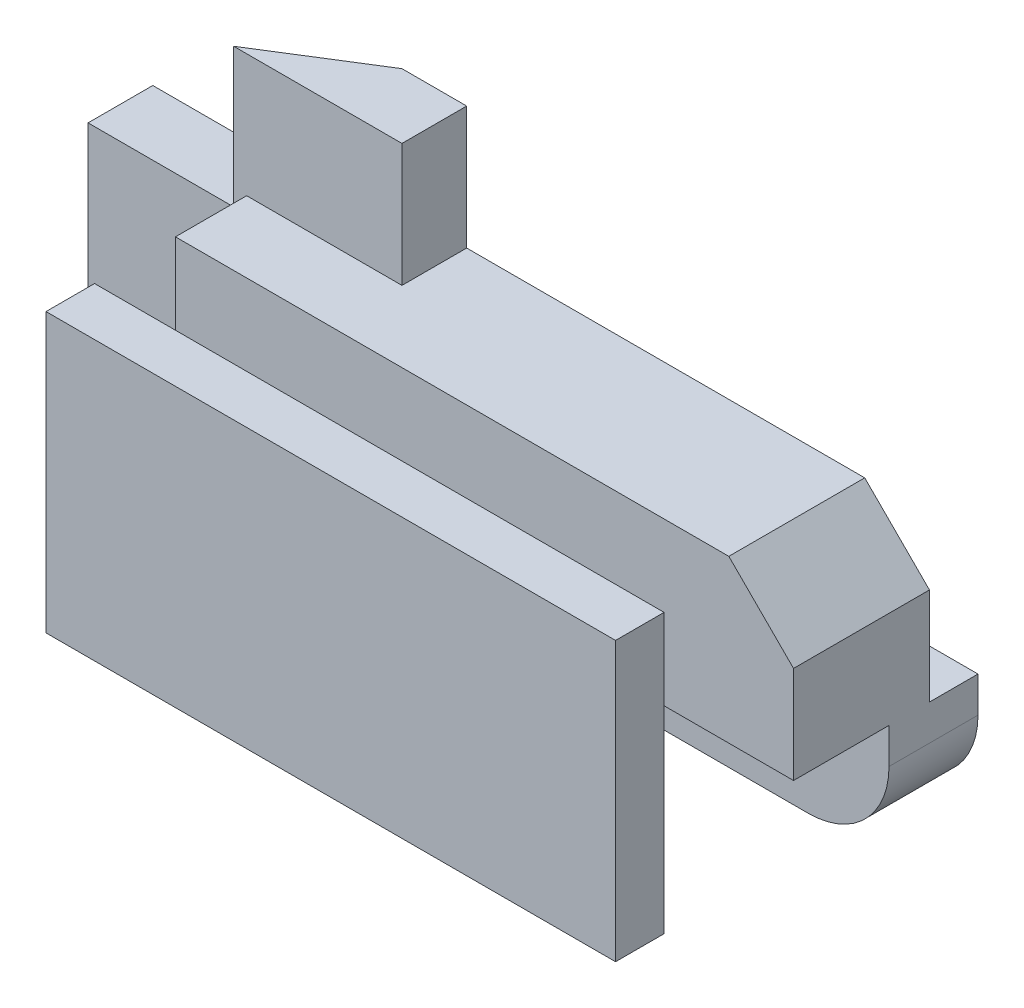
SolidWorks part; units mm, degrees
ref_plane "前视基准面" through (0, 0, 0) normal (0, 0, 1) x (1, 0, 0)
ref_plane "上视基准面" through (0, 0, 0) normal (0, 1, 0) x (1, 0, 0)
ref_plane "右视基准面" through (0, 0, 0) normal (1, 0, 0) x (0, 0, -1)
sketch "草图1" plane through (0, 0, 0) normal (0, 0, 1) x (1, 0, 0)
  line L1 (0, 0) -> (4.5, 0)
  line L2 (0, 0) -> (0, 6)
  line L3 (0, 6) -> (4.5, 6)
  line L4 (4.5, 0) -> (4.5, 6)
  line L5 (0, 0) -> (4.5, 6) construction
  line L6 (0, 6) -> (4.5, 0) construction
  point P4 (2.25, 3)
  dimension "D1" = 6
  dimension "D2" = 4.5
extrude "凸台-拉伸1" add sketch "草图1" along normal blind 2
sketch "草图2" plane through (0, 0, 0) normal (0, 0, -1) x (-1, 0, 0)
  line L0 (0, 6) -> (0, 0) construction
  line L1 (-4.5, 0) -> (-24, 0)
  line L2 (-4.5, 0) -> (-4.5, 6.5)
  line L3 (-4.5, 6.5) -> (-24, 6.5)
  line L4 (-24, 0) -> (-24, 6.5)
  line L5 (-4.5, 0) -> (-24, 6.5) construction
  line L6 (-4.5, 6.5) -> (-24, 0) construction
  point P4 (-14.25, 3.25)
  dimension "D1" = 6.5
  dimension "D2" = 24
extrude "凸台-拉伸2" add sketch "草图2" against normal blind 4.2
sketch "草图4" plane through (0, 0, 0) normal (0, 0, -1) x (-1, 0, 0)
  line L0 (0, 6) -> (0, 0) construction
  line L1 (-24, 0) -> (-14, 0)
  line L2 (-24, 0) -> (-24, -2.1)
  line L3 (-24, -2.1) -> (-14, -2.1)
  line L4 (-14, 0) -> (-14, -2.1)
  line L5 (-24, 0) -> (-14, -2.1) construction
  line L6 (-24, -2.1) -> (-14, 0) construction
  point P4 (-19, -1.05)
  dimension "D1" = 2.1
  dimension "D2" = 14
extrude "凸台-拉伸3" add sketch "草图4" against normal up to surface (4.2 mm away) up to face at (14.25, 3.25, 4.2)
sketch "草图5" plane through (0, 0, 4.2) normal (0, 0, 1) x (1, 0, 0)
  line L0 (0, 6) -> (0, 0) construction
  line L1 (0, 1.5) -> (24, 1.5)
  line L2 (0, 1.5) -> (0, -2.1)
  line L3 (0, -2.1) -> (24, -2.1)
  line L4 (24, 1.5) -> (24, -2.1)
  line L5 (0, 1.5) -> (24, -2.1) construction
  line L6 (0, -2.1) -> (24, 1.5) construction
  line L7 (0, 0) -> (4.5, 0) construction
  point P4 (12, -0.3)
  point P7 (24, -2.1)
  dimension "D1" = 1.5
extrude "切除-拉伸1" cut sketch "草图5" against normal offset from surface (2.95 mm away) 1.25 up to face at (10.625, 2.6, 0)
sketch "草图3" plane through (0, 0, 0) normal (0, 0, -1) x (-1, 0, 0)
  line L1 (-24, -2.1) -> (-19.5, -2.1)
  line L2 (-24, -2.1) -> (-24, 1.5)
  line L3 (-24, 1.5) -> (-19.5, 1.5)
  line L4 (-19.5, -2.1) -> (-19.5, 1.5)
  line L5 (-24, -2.1) -> (-19.5, 1.5) construction
  line L6 (-24, 1.5) -> (-19.5, -2.1) construction
  point P4 (-21.75, -0.3)
  point P6 (-24, -2.1)
  dimension "D1" = 4.5
  dimension "D2" = 3.6
extrude "凸台-拉伸4" add sketch "草图3" along normal blind 1.5
sketch "草图7" plane through (0, 0, 0) normal (0, 0, -1) x (-1, 0, 0)
  line L1 (-4.5, 6.5) -> (-9.7, 6.5)
  line L2 (-4.5, 6.5) -> (-4.5, 10.3)
  line L3 (-4.5, 10.3) -> (-9.7, 10.3)
  line L4 (-9.7, 6.5) -> (-9.7, 10.3)
  line L5 (-4.5, 6.5) -> (-9.7, 10.3) construction
  line L6 (-4.5, 10.3) -> (-9.7, 6.5) construction
  point P4 (-7.1, 8.4)
  dimension "D1" = 5.2
  dimension "D2" = 3.8
extrude "凸台-拉伸5" add sketch "草图7" against normal blind 2
sketch "草图8" plane through (0, 10.3, 0) normal (0, 1, 0) x (1, 0, 0)
  line L0 (4.5, -2) -> (7.7, 0)
  line L2 (4.5, 0) -> (9.7, 0) construction
  line L3 (7.7, 0) -> (4.5, 0)
  line L4 (4.5, 0) -> (4.5, -2)
  line L5 (9.7, -2) -> (9.7, 0) construction
  point P2 (4.5, -2)
  dimension "D1" = 2
extrude "切除-拉伸2" cut sketch "草图8" against normal up to surface (4.3 mm away) up to face at (2.25, 6, 1)
sketch "草图9" plane through (0, 0, 4.2) normal (0, 0, 1) x (1, 0, 0)
  line L0 (24, 1.5) -> (4.5, 1.5) construction
  line L1 (4.9, 1.5) -> (4.5, 1.5)
  line L2 (4.9, 1.5) -> (4.9, 6.5)
  line L3 (4.9, 6.5) -> (4.5, 6.5)
  line L4 (4.5, 1.5) -> (4.5, 6.5)
  line L5 (4.9, 1.5) -> (4.5, 6.5) construction
  line L6 (4.9, 6.5) -> (4.5, 1.5) construction
  line L7 (0, 6) -> (0, 1.5) construction
  point P4 (4.7, 4)
  dimension "D1" = 4.9
extrude "切除-拉伸3" cut sketch "草图9" against normal up to surface (2.2 mm away) up to face at (2.25, 3.75, 2)
fillet "圆角1" radius 2.5 1 edges at (24, -2.1, -0.125)
chamfer "倒角1" distance 2 angle 45 1 edges at (24, 6.5, 2.1)
sketch "草图10" plane through (0, 0, 4.2) normal (0, 0, 1) x (1, 0, 0)
  line L0 (24, 1.5) -> (0, 1.5) construction
  line L1 (7.74, 1.5) -> (16.94, 1.5)
  line L2 (7.74, 1.5) -> (7.74, 4)
  line L3 (7.74, 4) -> (16.94, 4)
  line L4 (16.94, 1.5) -> (16.94, 4)
  line L5 (7.74, 1.5) -> (16.94, 4) construction
  line L6 (7.74, 4) -> (16.94, 1.5) construction
  line L7 (4.9, 1.5) -> (4.9, 6.5) construction
  point P4 (12.34, 2.75)
  dimension "D1" = 2.84
  dimension "D2" = 9.2
  dimension "D3" = 2.5
extrude "凸台-拉伸6" add sketch "草图10" along normal blind 2.5
sketch "草图11" plane through (0, 0, 6.7) normal (0, 0, 1) x (1, 0, 0)
  line L0 (4.9, 6.5) -> (22, 6.5) construction
  line L1 (4.9, 6.5) -> (22.5, 6.5)
  line L2 (4.9, 6.5) -> (4.9, -2.1)
  line L3 (4.9, -2.1) -> (22.5, -2.1)
  line L4 (22.5, 6.5) -> (22.5, -2.1)
  line L5 (4.9, 6.5) -> (22.5, -2.1) construction
  line L6 (4.9, -2.1) -> (22.5, 6.5) construction
  point P4 (13.7, 2.2)
  point P5 (19.2623, 6.0859)
  point P8 (4.9, 6.5)
  dimension "D1" = 8.6
  dimension "D2" = 17.6
extrude "凸台-拉伸7" add sketch "草图11" along normal blind 1.5
